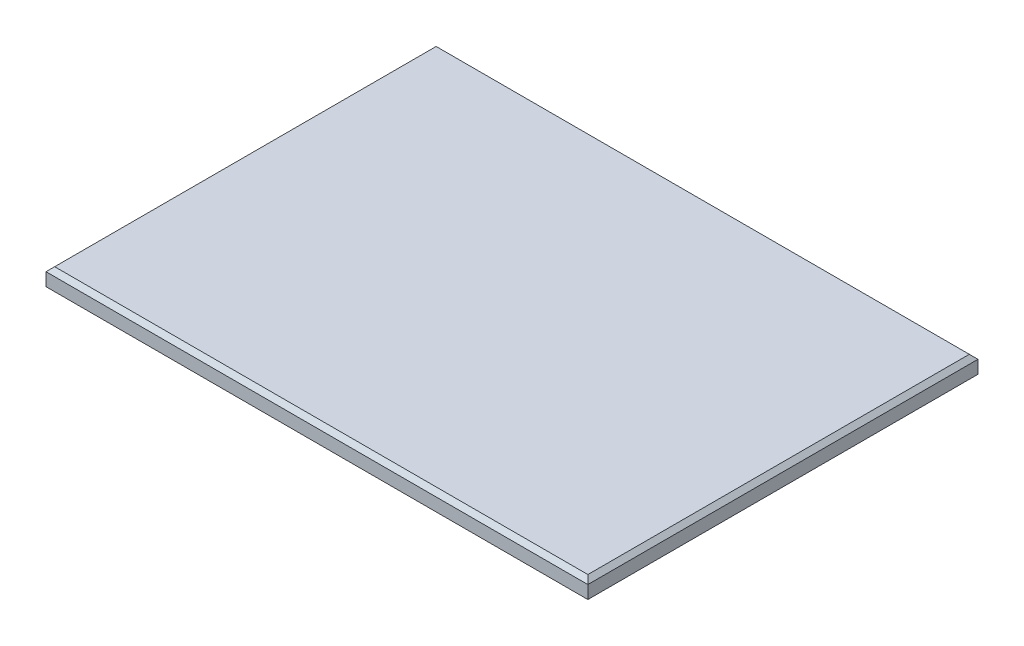
SolidWorks part; units mm, degrees
ref_plane "Front Plane" through (0, 0, 0) normal (0, 0, 1) x (1, 0, 0)
ref_plane "Top Plane" through (0, 0, 0) normal (0, 1, 0) x (1, 0, 0)
ref_plane "Right Plane" through (0, 0, 0) normal (1, 0, 0) x (0, 0, -1)
sketch "Sketch1" plane through (0, 0, 0) normal (0, 1, 0) x (1, 0, 0)
  line L1 (0, 0) -> (250, 0)
  line L2 (0, 0) -> (0, 180)
  line L3 (0, 180) -> (250, 180)
  line L4 (250, 0) -> (250, 180)
  dimension "D1" = 250
  dimension "D2" = 180
extrude "Boss-Extrude1" add sketch "Sketch1" along normal blind 10
chamfer "Chamfer1" distance 2 angle 45 8 edges at (125, 0, 0) (250, 0, -90) (125, 0, -180) (0, 0, -90) (125, 10, -180) (250, 10, -90) (125, 10, 0) (0, 10, -90)
